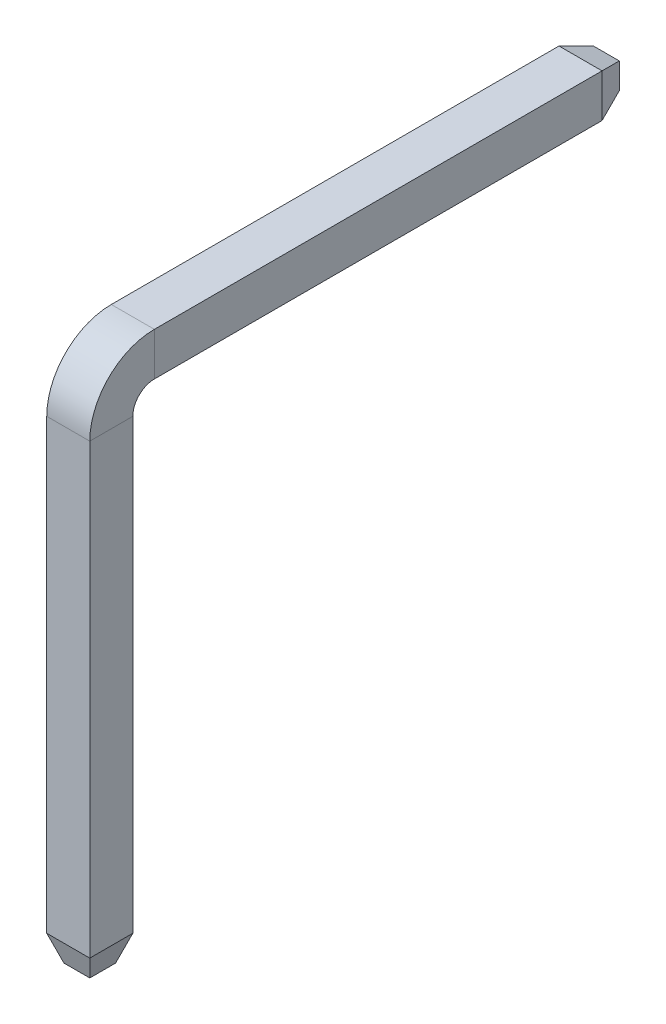
SolidWorks part; units mm, degrees
material "AISI 304"
ref_plane "Plano frontal" through (0, 0, 0) normal (0, 0, 1) x (1, 0, 0)
ref_plane "Plano superior" through (0, 0, 0) normal (0, 1, 0) x (1, 0, 0)
ref_plane "Plano direito" through (0, 0, 0) normal (1, 0, 0) x (0, 0, -1)
sketch "Esboço1" plane through (0, 0, 0) normal (1, 0, 0) x (0, 0, -1)
  line L0 (0, 0) -> (-5.5, 0)
  line L1 (-6, -0.5) -> (-6, -6)
  arc A0 (-5.5, 0) -> (-6, -0.5) centre (-5.5, -0.5) ccw
  point P6 (-6, 0)
  dimension "D3" = 0.5
  dimension "D1" = 6
  dimension "D2" = 6
sketch "Esboço2" plane through (0, 0, 0) normal (0, 0, 1) x (1, 0, 0)
  line L1 (-0.25, -0.25) -> (0.25, -0.25)
  line L2 (-0.25, -0.25) -> (-0.25, 0.25)
  line L3 (-0.25, 0.25) -> (0.25, 0.25)
  line L4 (0.25, -0.25) -> (0.25, 0.25)
  line L5 (-0.25, -0.25) -> (0.25, 0.25) construction
  line L6 (-0.25, 0.25) -> (0.25, -0.25) construction
  point P0 (0, 0)
  dimension "D1" = 0.5
  dimension "D2" = 0.5
sweep "Varredura1" add profiles "Esboço2" path "Esboço1"
chamfer "Chanfro1" distance 0.1 distance2 0.3 4 edges at (0, 0.25, 0) (-0.25, 0, 0) (0, -0.25, 0) (0.25, 0, 0)
chamfer "Chanfro2" distance 0.3 distance2 0.1 4 edges at (0, -6, 5.75) (-0.25, -6, 6) (0, -6, 6.25) (0.25, -6, 6)
